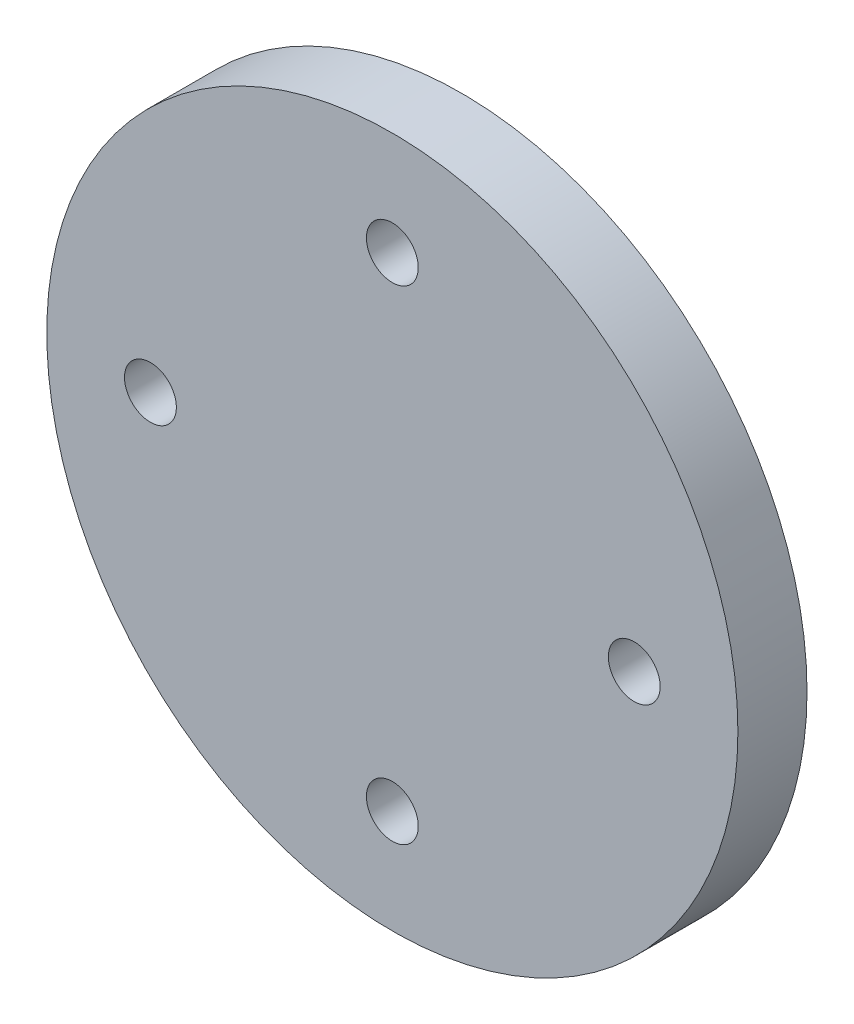
SolidWorks part; units mm, degrees
ref_plane "前视基准面" through (0, 0, 0) normal (0, 0, 1) x (1, 0, 0)
ref_plane "上视基准面" through (0, 0, 0) normal (0, 1, 0) x (1, 0, 0)
ref_plane "右视基准面" through (0, 0, 0) normal (1, 0, 0) x (0, 0, -1)
sketch "草图1" plane through (0, 0, 0) normal (0, 0, 1) x (1, 0, 0)
  circle A0 centre (0, 0) radius 10
  dimension "D1" = 20
extrude "凸台-拉伸1" add sketch "草图1" along normal blind 2
sketch "草图2" plane through (0, 0, 0) normal (0, 0, -1) x (-1, 0, 0)
  circle A0 centre (0, 0) radius 4
extrude "凸台-拉伸2" add sketch "草图2" along normal blind 2
sketch "草图3" plane through (0, 0, -2) normal (0, 0, -1) x (-1, 0, 0)
  circle A0 centre (0, 0) radius 3.05
extrude "切除-拉伸1" cut sketch "草图3" against normal blind 3.5
sketch "草图4" plane through (0, 0, 0) normal (0, 0, -1) x (-1, 0, 0)
  circle A0 centre (0, 7) radius 0.75
  circle A1 centre (7, 0) radius 0.75
  circle A2 centre (0, -7) radius 0.75
  circle A3 centre (-7, 0) radius 0.75
  point P2 (0, 0)
  point P3 (0, 0)
  point P11 (0, 0)
  dimension "D1" = 4
  dimension "D2" = 7
extrude "切除-拉伸2" cut sketch "草图4" against normal through all
